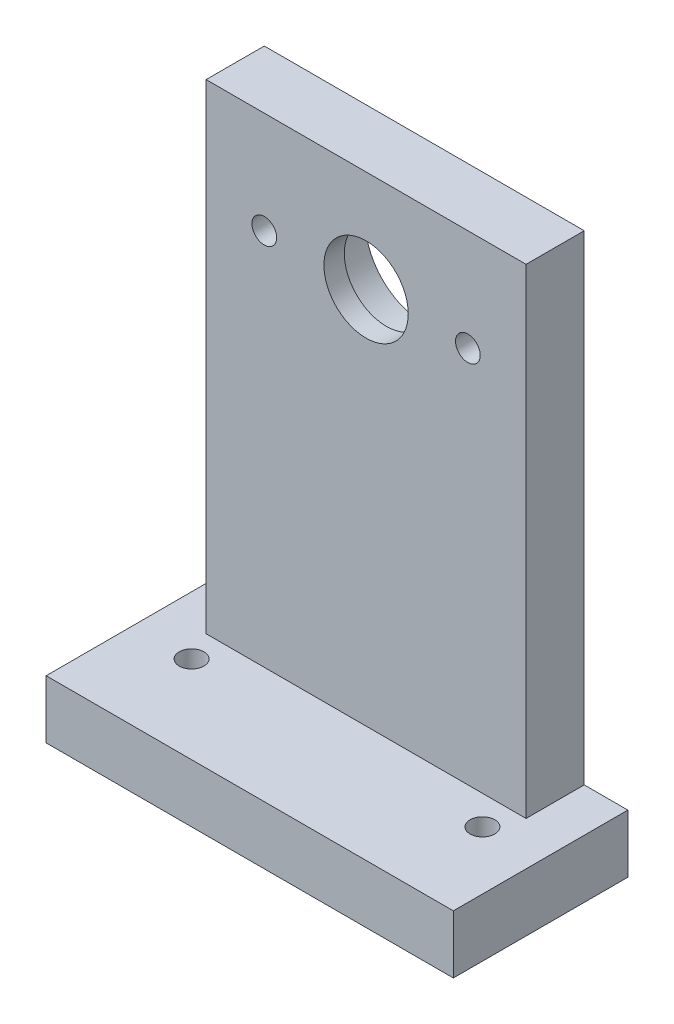
SolidWorks part; units mm, degrees
ref_plane "前视基准面" through (0, 0, 0) normal (0, 0, 1) x (1, 0, 0)
ref_plane "上视基准面" through (0, 0, 0) normal (0, 1, 0) x (1, 0, 0)
ref_plane "右视基准面" through (0, 0, 0) normal (1, 0, 0) x (0, 0, -1)
other "Configuration Table"
sketch "草图1" plane through (0, 0, 0) normal (0, 0, 1) x (1, 0, 0)
  line L1 (-28, 0) -> (28, 0)
  line L2 (-28, 0) -> (-28, 8)
  line L3 (-28, 8) -> (28, 8)
  line L4 (28, 0) -> (28, 8)
extrude "Foot_56x24x8" add sketch "草图1" along normal blind 24
sketch "草图2" plane through (0, 0, 0) normal (0, 0, 1) x (1, 0, 0)
  line L1 (-22, 0) -> (22, 0)
  line L2 (-22, 0) -> (-22, 74)
  line L3 (-22, 74) -> (22, 74)
  line L4 (22, 0) -> (22, 74)
extrude "Tower_pivot_height60" add sketch "草图2" along normal blind 8
sketch "草图3" plane through (0, 0, 0) normal (0, 0, 1) x (1, 0, 0)
  circle A0 centre (0, 60) radius 5.8
  circle A1 centre (-14, 60) radius 1.7
  circle A2 centre (14, 60) radius 1.7
extrude "Shaft_access_and_retainer_M3" cut sketch "草图3" against normal through all and the other way through all
sketch "草图4" plane through (0, 0, 0) normal (0, 0, 1) x (1, 0, 0)
  circle A0 centre (0, 60) radius 8.1
extrude "625ZZ_pocket_D16p2_depth5p2_TEST_FIT" cut sketch "草图4" along normal blind 5.2
sketch "草图5" plane through (0, 0, 0) normal (0, 1, 0) x (1, 0, 0)
  circle A0 centre (-20, -12) radius 1.7
  circle A1 centre (20, -12) radius 1.7
extrude "Foot_M3_through" cut sketch "草图5" against normal through all and the other way through all
